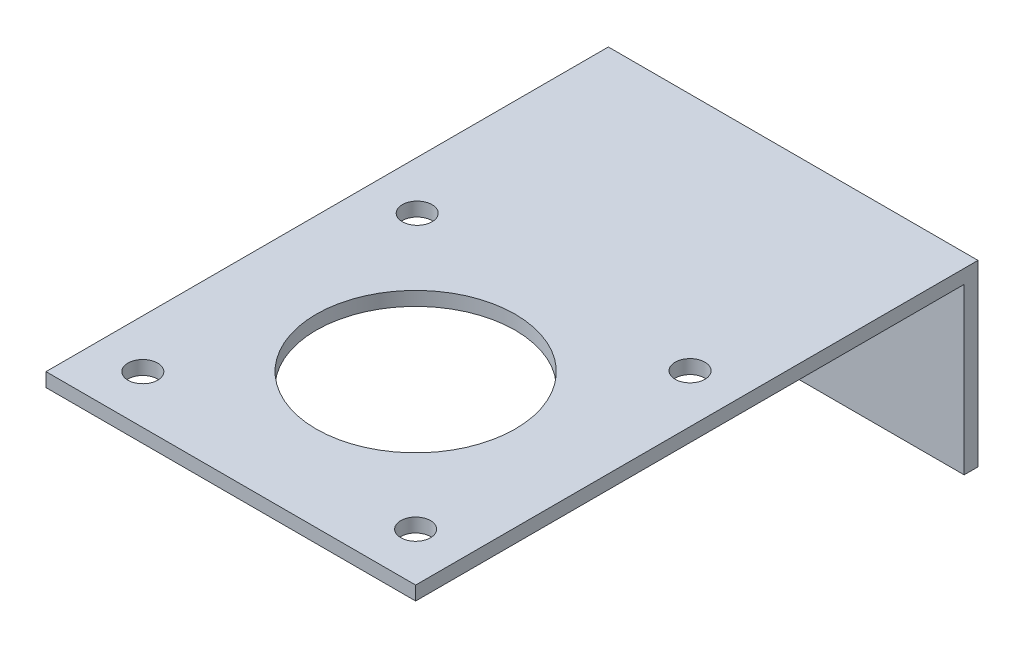
SolidWorks part; units mm, degrees
ref_plane "Front Plane" through (0, 0, 0) normal (1, 0, 0) x (0, 1, 0)
ref_plane "Top Plane" through (0, 0, 0) normal (0, 0, 1) x (0, 1, 0)
ref_plane "Right Plane" through (0, 0, 0) normal (0, 1, 0) x (-1, 0, 0)
sketch "Sketch1" plane through (0, 0, 0) normal (0, 0, 1) x (0, 1, 0)
  line L1 (-10.16, 21) -> (10.16, 21)
  line L2 (-10.16, 21) -> (-10.16, -21)
  line L3 (-10.16, -21) -> (10.16, -21)
  line L4 (10.16, 21) -> (10.16, -21)
  line L5 (-10.16, 21) -> (10.16, -21) construction
  line L6 (-10.16, -21) -> (10.16, 21) construction
  point P0 (0, 0)
  dimension "D1" = 42
  dimension "D2" = 20.32
extrude "Boss-Extrude1" add sketch "Sketch1" along normal blind 1.5748
sketch "Sketch2" plane through (0, 0, 1.5748) normal (0, 0, 1) x (1, 0, 0)
  line L0 (21, -10.16) -> (21, 10.16) construction
  line L1 (-21, 10.16) -> (21, 10.16)
  line L2 (-21, 10.16) -> (-21, 8.5852)
  line L3 (-21, 8.5852) -> (21, 8.5852)
  line L4 (21, 10.16) -> (21, 8.5852)
  dimension "D1" = 1.5748
extrude "Boss-Extrude2" add sketch "Sketch2" along normal blind 62.32
sketch "Sketch3" plane through (0, 8.5852, 0) normal (0, -1, 0) x (-1, 0, 0)
  line L2 (21, -63.8948) -> (-21, -63.8948) construction
  line L4 (-21, -63.8948) -> (-21, -1.5748) construction
  line L5 (0, -63.8948) -> (0, -1.5748) construction
  line L6 (21, -1.5748) -> (-21, -1.5748) construction
  circle A0 centre (0, -42.8918) radius 11.303
  circle A1 centre (-15.5009, -58.3957) radius 1.6891
  circle A2 centre (-15.5009, -27.2175) radius 1.6891
  circle A3 centre (15.5009, -27.2175) radius 1.6891
  circle A4 centre (15.5009, -58.3957) radius 1.6891
  dimension "D1" = 22.606
  dimension "D2" = 21.003
  dimension "D3" = 3.3782
  dimension "D4" = 5.4991
  dimension "D5" = 5.4991
  dimension "D6" = 3.3782
  dimension "D7" = 31.1782
extrude "Cut-Extrude1" cut sketch "Sketch3" against normal blind 62.32 contours A1 | A0 | A2 | A3 | A4
sketch "Sketch4" plane through (0, 0, 1.5748) normal (0, 0, 1) x (1, 0, 0)
  line L0 (0, 0) -> (0, -10.16) construction
  line L1 (-21, -10.16) -> (21, -10.16) construction
  circle A0 centre (9.035, 0) radius 2.05
  circle A1 centre (-9.035, 0) radius 2.05
  dimension "D1" = 4.1
  dimension "D2" = 9.035
extrude "Cut-Extrude2" cut sketch "Sketch4" against normal blind 62.32 contours A0 | A1
